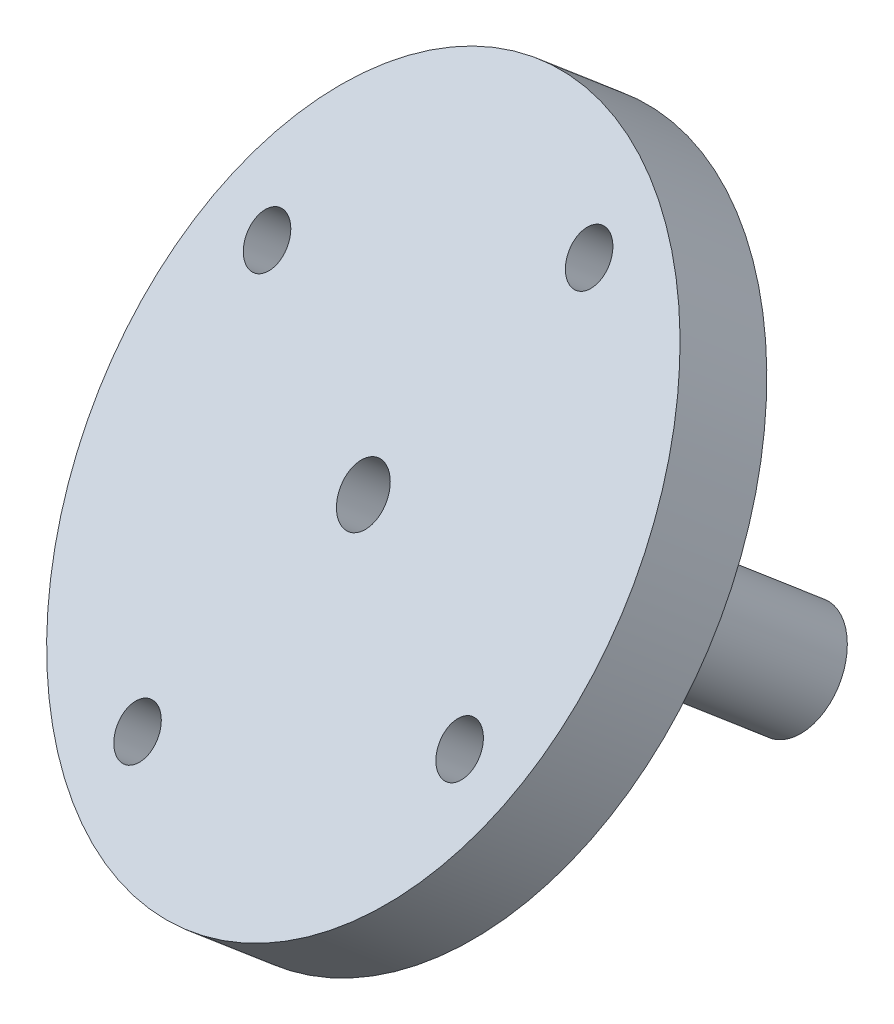
SolidWorks part; units mm, degrees
ref_plane "Front Plane" through (0, 0, 0) normal (0, 0, 1) x (1, 0, 0)
ref_plane "Top Plane" through (0, 0, 0) normal (0, 1, 0) x (1, 0, 0)
ref_plane "Right Plane" through (0, 0, 0) normal (1, 0, 0) x (0, 0, -1)
sketch "Sketch2" plane through (1017.7354, -1937.1836, -1858.3452) normal (0.2935, -0.5915, -0.751) x (0.856, -0.1872, 0.4819)
  circle A0 centre (34.0176, 1.1866) radius 20
  circle A1 centre (34.0176, 16.6866) radius 1.5
  circle A3 centre (49.5176, 1.1866) radius 1.5
  circle A4 centre (34.0176, -14.3134) radius 1.5
  circle A5 centre (18.5176, 1.1866) radius 1.5
  circle A6 centre (34.0176, 1.1866) radius 1.7
  point P14 (34.0176, 1.1866)
  dimension "D1" = 40
  dimension "D3" = 3
  dimension "D2" = 15.5
  dimension "D4" = 4
extrude "Boss-Extrude1" add sketch "Sketch2" along normal blind 5
sketch "Sketch3" plane through (834.9863, -1682.8904, -2136.7023) normal (0.2935, -0.5915, -0.751) x (-0.2325, 0.7179, -0.6562)
  circle A0 centre (-430.6951, 121.5543) radius 3.175
  circle A1 centre (-430.6951, 121.5543) radius 1.7 construction
  circle A2 centre (-430.6951, 121.5543) radius 1.7
extrude "Boss-Extrude2" add sketch "Sketch3" along normal blind 20
